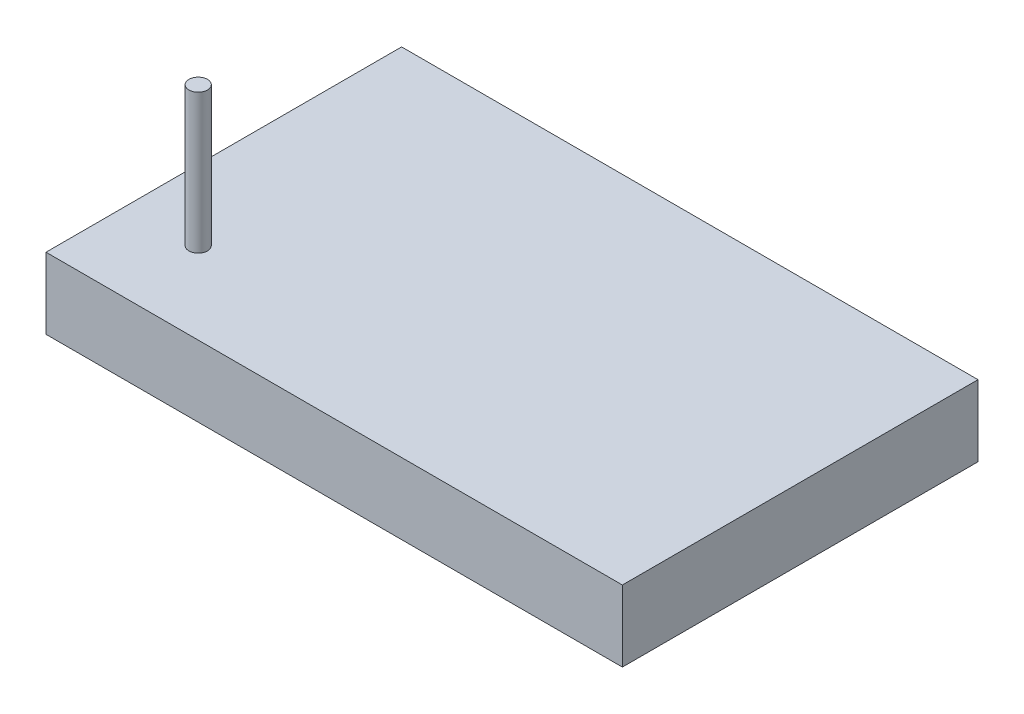
SolidWorks part; units mm, degrees
ref_plane "Front Plane" through (0, 0, 0) normal (0, 0, 1) x (1, 0, 0)
ref_plane "Top Plane" through (0, 0, 0) normal (0, 1, 0) x (1, 0, 0)
ref_plane "Right Plane" through (0, 0, 0) normal (1, 0, 0) x (0, 0, -1)
sketch "Sketch1" plane through (0, 0, 0) normal (0, 1, 0) x (1, 0, 0)
  line L1 (0, 0) -> (101.3, 0)
  line L2 (0, 0) -> (0, 62.5)
  line L3 (0, 62.5) -> (101.3, 62.5)
  line L4 (101.3, 0) -> (101.3, 62.5)
  dimension "D1" = 101.3
  dimension "D2" = 62.5
extrude "Boss-Extrude1" add sketch "Sketch1" along normal blind 12.5
sketch "Sketch2" plane through (0, 12.5, 0) normal (0, 1, 0) x (1, 0, 0)
  line L0 (0, 62.5) -> (0, 0) construction
  line L1 (0, 0) -> (101.3, 0) construction
  circle A0 centre (12.375, 14.375) radius 1.625
  dimension "D1" = 3.25
  dimension "D2" = 12.375
  dimension "D3" = 14.375
extrude "Boss-Extrude2" add sketch "Sketch2" along normal blind 24.5
